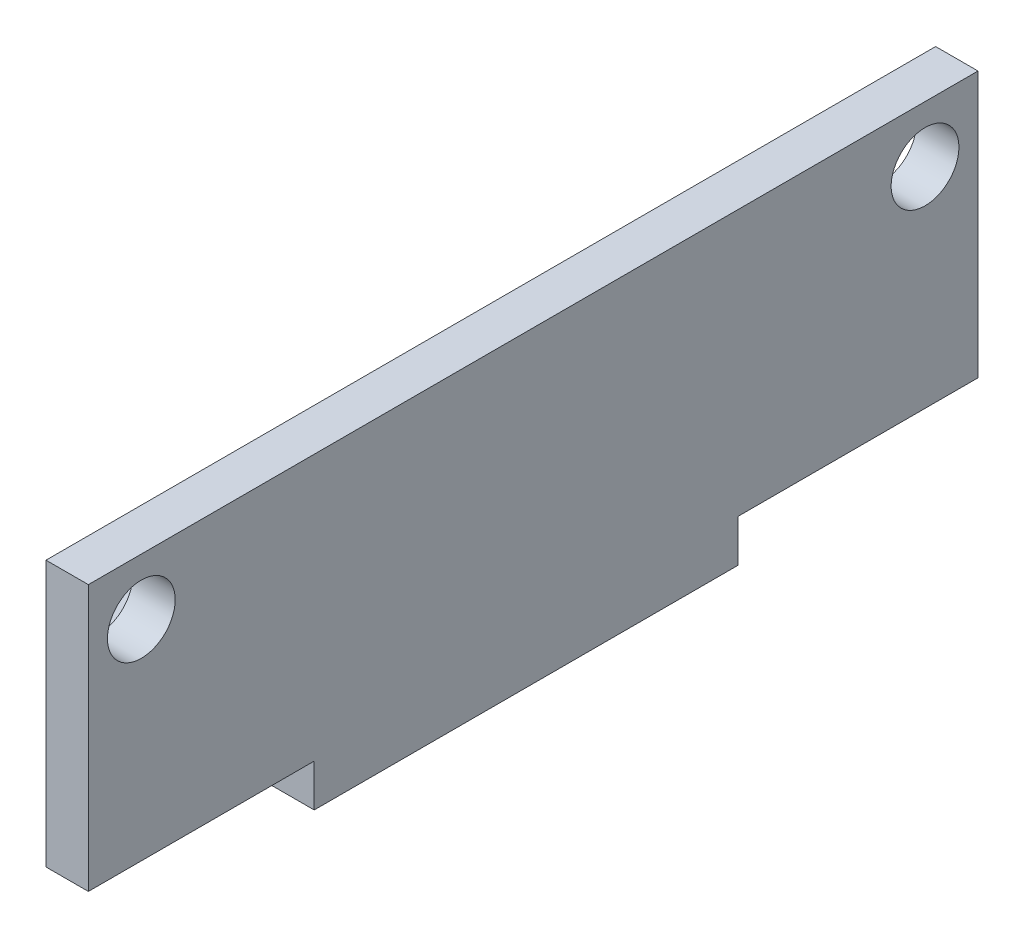
SolidWorks part; units mm, degrees
ref_plane "前视基准面" through (0, 0, 0) normal (0, 0, 1) x (1, 0, 0)
ref_plane "上视基准面" through (0, 0, 0) normal (0, 1, 0) x (1, 0, 0)
ref_plane "右视基准面" through (0, 0, 0) normal (1, 0, 0) x (0, 0, -1)
sketch "草图1" plane through (0, 0, 0) normal (0, 1, 0) x (1, 0, 0)
  line L1 (-6, -10) -> (6, -10)
  line L2 (-6, -10) -> (-6, 10)
  line L3 (-6, 10) -> (6, 10)
  line L4 (6, -10) -> (6, 10)
  line L5 (-6, -10) -> (6, 10) construction
  line L6 (-6, 10) -> (6, -10) construction
  point P0 (0, 0)
extrude "凸台-拉伸1" add sketch "草图1" along normal blind 2
sketch "草图2" plane through (0, 2, 0) normal (0, 1, 0) x (1, 0, 0)
  line L0 (-6, -10) -> (6, -10) construction
  line L1 (6, 10) -> (8, 10)
  line L2 (6, 10) -> (6, -10)
  line L3 (6, -10) -> (8, -10)
  line L5 (4, -20.6623) -> (6, -20.6623)
  line L6 (4, -20.6623) -> (4, 21.3377)
  line L7 (4, 21.3377) -> (6, 21.3377)
  line L8 (6, -20.6623) -> (6, 21.3377)
  line L9 (4, -20.6623) -> (6, 21.3377) construction
  line L10 (4, 21.3377) -> (6, -20.6623) construction
  point P7 (5, 0.3377)
  line M1 (6, -10) -> (6, 10)
  line M2 (6, 10) -> (-6, 10)
  line M4 (-6, -10) -> (6, -10)
  dimension "D1" = 2
  dimension "D2" = 42
  dimension "D3" = 0
extrude "凸台-拉伸3" add sketch "草图2" along normal blind 20 contours L8 L7 L6 M2 | L6 M4 M1 M2 | L5 L8 L6 M4
sketch "草图5" plane through (6, 0, 0) normal (1, 0, 0) x (0, 0, -1)
  line L0 (-20.6623, 22) -> (-20.6623, 2) construction
  line L1 (21.3377, 22) -> (21.3377, 2) construction
  line L3 (-20.6623, 22) -> (21.3377, 22)
  line L4 (-20.6623, 22) -> (-20.6623, 14.5454)
  line L5 (-20.6623, 14.5454) -> (21.3377, 14.5454)
  line L6 (21.3377, 22) -> (21.3377, 14.5454)
  circle A0 centre (-18.1623, 11.8823) radius 1.6
  circle A1 centre (18.8377, 11.8823) radius 1.6
  point P4 (-20.6623, 12)
  dimension "D1" = 2.5
  dimension "D2" = 2.5
extrude "切除-拉伸1" cut sketch "草图5" against normal blind 20
sketch "草图6" plane through (0, 2, 0) normal (0, 1, 0) x (1, 0, 0)
  line L0 (4, 10) -> (-6, 10) construction
  line L1 (-6, -10) -> (4, -10) construction
  circle A0 centre (-2.6204, 5) radius 1.6
  circle A1 centre (-2.6204, -5) radius 1.6
  dimension "D1" = 5
  dimension "D2" = 5
  dimension "D3" = 0
extrude "切除-拉伸2" cut sketch "草图6" against normal blind 10
